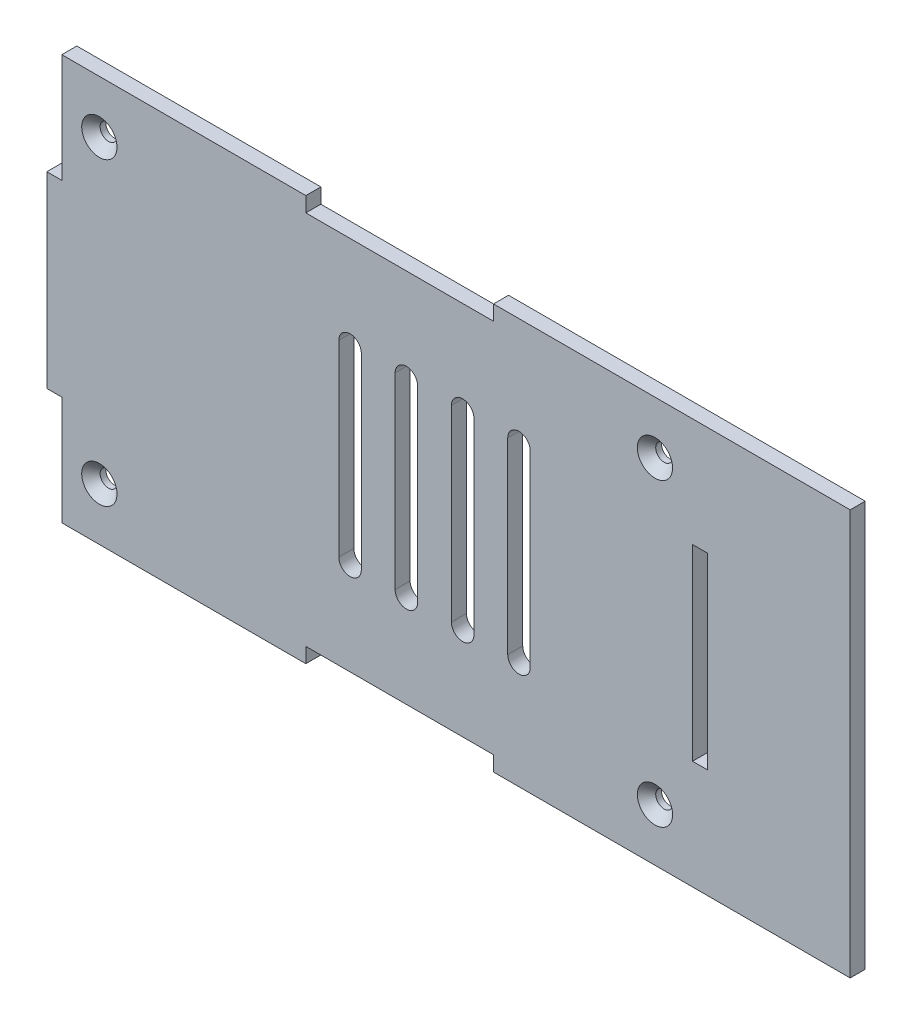
SolidWorks part; units mm, degrees
ref_plane "Front Plane" through (0, 0, 0) normal (0, 0, 1) x (1, 0, 0)
ref_plane "Top Plane" through (0, 0, 0) normal (0, 1, 0) x (1, 0, 0)
ref_plane "Right Plane" through (0, 0, 0) normal (1, 0, 0) x (0, 0, -1)
sketch "Sketch1" plane through (0, 0, 0) normal (0, 0, 1) x (1, 0, 0)
  line L1 (0, -25) -> (0, 25)
  line L2 (0, 25) -> (4, 25)
  line L3 (4, 25) -> (4, 54)
  line L4 (4, 54) -> (69, 54)
  line L5 (69, 54) -> (69, 50)
  line L6 (69, 50) -> (119, 50)
  line L7 (119, 50) -> (119, 54)
  line L8 (119, 54) -> (214, 54)
  line L9 (214, 54) -> (214, -54)
  line L16 (0, 0) -> (214, 0)
  line L17 (119, -54) -> (214, -54)
  line L18 (119, -50) -> (119, -54)
  line L19 (69, -50) -> (119, -50)
  line L20 (69, -54) -> (69, -50)
  line L21 (4, -54) -> (69, -54)
  line L22 (4, -25) -> (4, -54)
  line L23 (0, -25) -> (4, -25)
  dimension "D1" = 4
  dimension "D2" = 4
  dimension "D3" = 25
  dimension "D4" = 50
  dimension "D5" = 29
  dimension "D6" = 65
  dimension "D7" = 95
extrude "Boss-Extrude1" add sketch "Sketch1" along normal blind 4 contours L1 L16 L9 L8 L7 L6 L5 L4 L3 L2 | L1 L23 L22 L21 L20 L19 L18 L17 L9 L16
sketch "Sketch2" plane through (0, 0, 4) normal (0, 0, 1) x (1, 0, 0)
  line L0 (174, 0) -> (0, 0)
  line L1 (172, -25) -> (176, -25)
  line L2 (172, -25) -> (172, 25)
  line L3 (172, 25) -> (176, 25)
  line L4 (176, -25) -> (176, 25)
  line L5 (172, -25) -> (176, 25) construction
  line L6 (172, 25) -> (176, -25) construction
  line L7 (0, -25) -> (0, 25) construction
  line L8 (4, 25) -> (4, 54) construction
  point P0 (174, 0)
  dimension "D1" = 4
  dimension "D2" = 50
  dimension "D3" = 168
extrude "Cut-Extrude1" cut sketch "Sketch2" against normal up to next
sketch "Sketch3" plane through (0, 0, 4) normal (0, 0, 1) x (1, 0, 0)
  line L0 (69, 50) -> (119, 50) construction
  line L1 (14, -40) -> (162, -40)
  line L2 (14, -40) -> (14, 40)
  line L3 (14, 40) -> (162, 40)
  line L4 (162, -40) -> (162, 40)
  line L5 (4, 25) -> (4, 54) construction
  line L6 (172, -25) -> (172, 25) construction
  line L7 (69, -50) -> (119, -50) construction
  dimension "D1" = 10
  dimension "D2" = 10
  dimension "D3" = 10
  dimension "D4" = 10
hole_wizard "CSK for M4 Countersunk Flat Head Screw1" positions "3DSketch1" profile "Sketch4" countersink size "M4" standard "ISO" end condition up to next
sketch3d "3DSketch1"
  point P0 (14, 40, 4)
  point P3 (162, 40, 4)
  point P6 (162, -40, 4)
  point P9 (14, -40, 4)
sketch "Sketch4" plane through (14, 40, 4) normal (1, 0, 0) x (0, -1, 0)
  line L0 (0, 0) -> (0, 4)
  line L1 (0, 4) -> (2.25, 4)
  line L2 (2.25, 4) -> (2.25, 2.45)
  line L3 (2.25, 2.45) -> (4.7, 0)
  line L5 (4.7, 0) -> (0, 0)
  line L6 (-2.25, 2.45) -> (-4.7, 0) construction
  line L11 (0, -6.35) -> (0, 107.95) construction
  dimension "Thru Hole Dia." = 4.5
  dimension "Thru Hole Depth" = 4
  dimension "Near C'Sink Dia." = 9.4
  dimension "Near C'Sink Angle" = 90
sketch "Sketch5" plane through (0, 0, 0) normal (0, 0, -1) x (-1, 0, 0)
  line L0 (-125.777, 25) -> (-125.777, -25) construction
  line L1 (-122.777, 25) -> (-122.777, -25)
  line L2 (-128.777, 25) -> (-128.777, -25)
  line L3 (-125.777, 0) -> (0, 0)
  line L4 (-113.777, 25) -> (-113.777, -25)
  line L5 (-107.777, 25) -> (-107.777, -25)
  line L6 (-110.777, 25) -> (-110.777, -25) construction
  line L7 (-98.777, 25) -> (-98.777, -25)
  line L8 (-92.777, 25) -> (-92.777, -25)
  line L9 (-95.777, 25) -> (-95.777, -25) construction
  line L10 (-83.777, 25) -> (-83.777, -25)
  line L11 (-77.777, 25) -> (-77.777, -25)
  line L12 (-80.777, 25) -> (-80.777, -25) construction
  arc A0 (-122.777, 25) -> (-128.777, 25) centre (-125.777, 25) ccw
  arc A1 (-128.777, -25) -> (-122.777, -25) centre (-125.777, -25) ccw
  arc A2 (-107.777, 25) -> (-113.777, 25) centre (-110.777, 25) ccw
  arc A3 (-113.777, -25) -> (-107.777, -25) centre (-110.777, -25) ccw
  arc A4 (-92.777, 25) -> (-98.777, 25) centre (-95.777, 25) ccw
  arc A5 (-98.777, -25) -> (-92.777, -25) centre (-95.777, -25) ccw
  arc A6 (-77.777, 25) -> (-83.777, 25) centre (-80.777, 25) ccw
  arc A7 (-83.777, -25) -> (-77.777, -25) centre (-80.777, -25) ccw
  point P2 (-125.777, 0)
  point P14 (-110.777, 0)
  point P21 (-95.777, 0)
  point P28 (-80.777, 0)
  dimension "D1" = 3
  dimension "D2" = 50
  dimension "D3" = 4
extrude "Cut-Extrude2" cut sketch "Sketch5" against normal up to next
